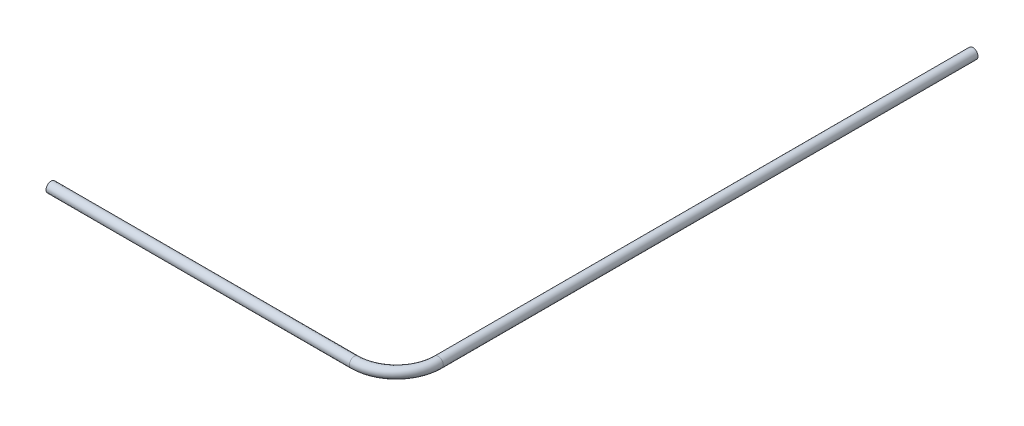
SolidWorks part; units mm, degrees
material "AISI 1020"
ref_plane "Спереди" through (0, 0, 0) normal (0, 0, 1) x (1, 0, 0)
ref_plane "Сверху" through (0, 0, 0) normal (0, 1, 0) x (1, 0, 0)
ref_plane "Справа" through (0, 0, 0) normal (1, 0, 0) x (0, 0, -1)
sketch "Эскиз1" plane through (0, 0, 0) normal (0, 1, 0) x (1, 0, 0)
  line L0 (12, 250) -> (12, -388)
  line L1 (-38, -438) -> (-400, -438)
  arc A0 (12, -388) -> (-38, -438) centre (-38, -388) cw
  dimension "D5" = 50
  dimension "D1" = 250
  dimension "D2" = 12
  dimension "D3" = 12
  dimension "D4" = 250
sketch "Эскиз2" plane through (150, -150, 0) normal (0, 0, 1) x (1, 0, 0)
  circle A0 centre (-138, 150) radius 6
  circle A1 centre (-150, 150) radius 6 construction
sweep "По траектории1" add profiles "Эскиз2" path "Эскиз1"
